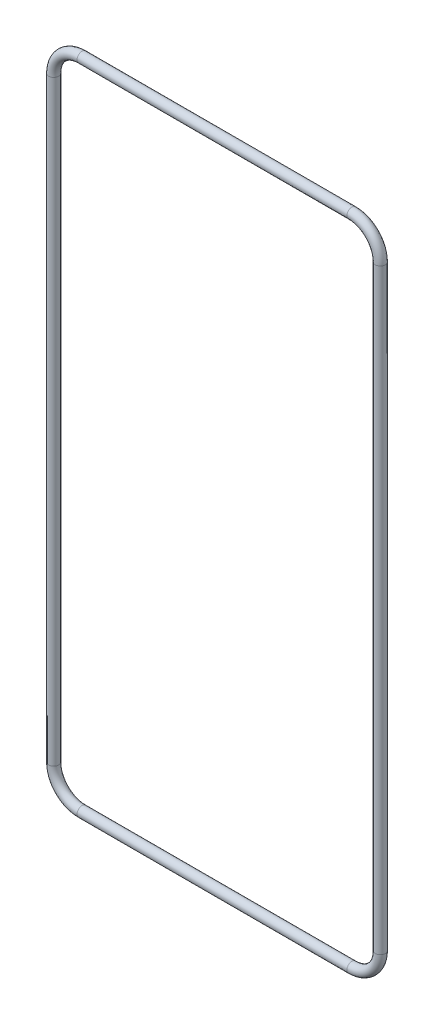
SolidWorks part; units mm, degrees
material "VITON"
ref_plane "Plano frontal" through (0, 0, 0) normal (0, 0, 1) x (1, 0, 0)
ref_plane "Plano superior" through (0, 0, 0) normal (0, 1, 0) x (1, 0, 0)
ref_plane "Plano direito" through (0, 0, 0) normal (1, 0, 0) x (0, 0, -1)
sketch "Esboço1" plane through (0, 0, 0) normal (0, 0, 1) x (1, 0, 0)
  line L1 (-55.9977, -123.7185) -> (39.0023, -123.7185)
  line L2 (-65.9977, -113.7185) -> (-65.9977, 96.2815)
  line L3 (-55.9977, 106.2815) -> (39.0023, 106.2815)
  line L4 (49.0023, -113.7185) -> (49.0023, 96.2815)
  line L5 (-65.9977, -123.7185) -> (49.0023, 106.2815) construction
  line L6 (-65.9977, 106.2815) -> (49.0023, -123.7185) construction
  arc A0 (-65.9977, -113.7185) -> (-55.9977, -123.7185) centre (-55.9977, -113.7185) ccw
  arc A1 (49.0023, -113.7185) -> (39.0023, -123.7185) centre (39.0023, -113.7185) cw
  arc A2 (49.0023, 96.2815) -> (39.0023, 106.2815) centre (39.0023, 96.2815) ccw
  arc A3 (-55.9977, 106.2815) -> (-65.9977, 96.2815) centre (-55.9977, 96.2815) ccw
  point P0 (-8.4977, -8.7185)
  dimension "D3" = 10
  dimension "D1" = 230
  dimension "D2" = 115
sketch "Esboço2" plane through (0, 0, 0) normal (0, 1, 0) x (1, 0, 0)
  line L0 (-65.9977, 0) -> (49.0023, 0) construction
  circle A0 centre (49.0023, 0) radius 1.765
  dimension "D1" = 3.53
sweep "Varredura1" add profiles "Esboço2" path "Esboço1"
